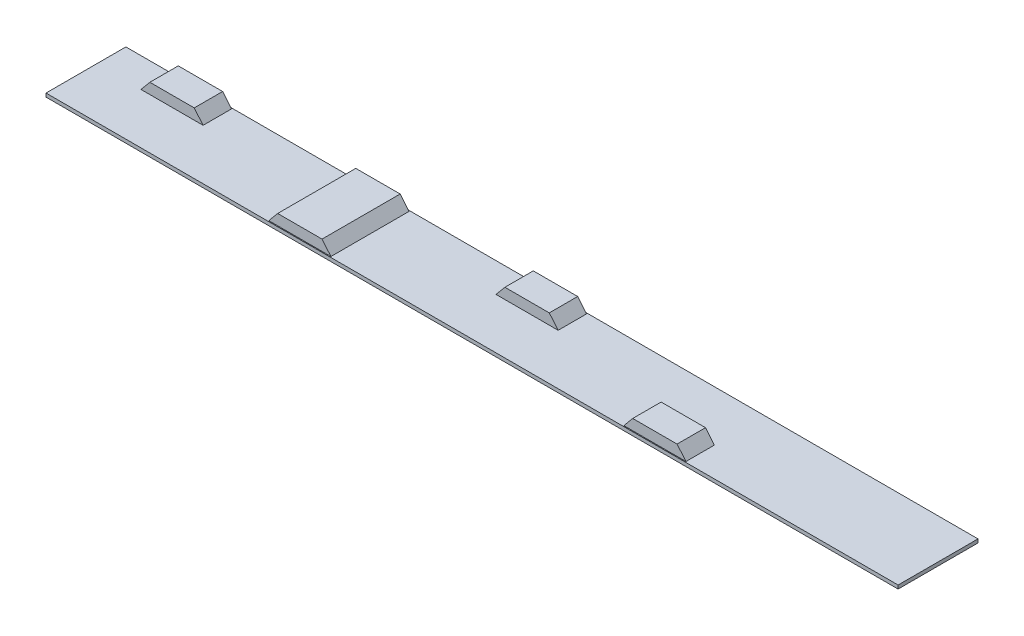
SolidWorks part; units mm, degrees
ref_plane "Front Plane" through (0, 0, 0) normal (0, 0, 1) x (1, 0, 0)
ref_plane "Top Plane" through (0, 0, 0) normal (0, 1, 0) x (1, 0, 0)
ref_plane "Right Plane" through (0, 0, 0) normal (1, 0, 0) x (0, 0, -1)
sketch "Sketch1" plane through (0, 0, 0) normal (0, 1, 0) x (1, 0, 0)
  line L1 (1200, -112.5) -> (-1200, -112.5)
  line L2 (1200, -112.5) -> (1200, 112.5)
  line L3 (1200, 112.5) -> (-1200, 112.5)
  line L4 (-1200, -112.5) -> (-1200, 112.5)
  line L5 (1200, -112.5) -> (-1200, 112.5) construction
  line L6 (1200, 112.5) -> (-1200, -112.5) construction
  point P0 (0, 0)
  dimension "D1" = 2400
  dimension "D2" = 225
extrude "Boss-Extrude1" add sketch "Sketch1" along normal blind 10
sketch "Sketch2" plane through (0, 0, 0) normal (0, 0, 1) x (1, 0, 0)
  line L0 (425, 10) -> (450, 40)
  line L1 (-1200, 10) -> (1200, 10) construction
  line L2 (450, 40) -> (575, 40)
  line L3 (575, 40) -> (600, 10)
  line L4 (600, 10) -> (425, 10)
  line L5 (1200, 10) -> (1200, 0) construction
  dimension "D1" = 175
  dimension "D2" = 125
  dimension "D3" = 30
  dimension "D4" = 600
extrude "Boss-Extrude2" add sketch "Sketch2" along normal blind 80 from offset 30
sketch "Sketch3" plane through (0, 0, 0) normal (0, 0, 1) x (1, 0, 0)
  line L0 (-50, 40) -> (-75, 10)
  line L1 (75, 40) -> (-50, 40)
  line L2 (100, 10) -> (75, 40)
  line L3 (-75, 10) -> (100, 10)
  line L4 (450, 40) -> (425, 10)
  line L5 (575, 40) -> (450, 40)
  line L6 (600, 10) -> (575, 40)
  line L7 (425, 10) -> (600, 10)
  line L8 (450, 40) -> (425, 10) construction
  line L9 (575, 40) -> (450, 40) construction
  line L10 (600, 10) -> (575, 40) construction
  line L11 (425, 10) -> (600, 10) construction
  dimension "D1" = 0
  dimension "D2" = 2
extrude "Boss-Extrude3" add sketch "Sketch3" against normal blind 80 from offset 30 offset against normal yes
sketch "Sketch4" plane through (0, 0, 0) normal (0, 0, 1) x (1, 0, 0)
  line L0 (-550, 40) -> (-575, 10)
  line L1 (-425, 40) -> (-550, 40)
  line L2 (-400, 10) -> (-425, 40)
  line L3 (-575, 10) -> (-400, 10)
  line L4 (450, 40) -> (425, 10)
  line L5 (575, 40) -> (450, 40)
  line L6 (600, 10) -> (575, 40)
  line L7 (425, 10) -> (600, 10)
  line L8 (450, 40) -> (425, 10) construction
  line L9 (575, 40) -> (450, 40) construction
  line L10 (600, 10) -> (575, 40) construction
  line L11 (425, 10) -> (600, 10) construction
  dimension "D1" = 0
extrude "Boss-Extrude4" add sketch "Sketch4" along normal blind 110 and the other way blind 110
sketch "Sketch5" plane through (0, 0, 0) normal (0, 0, 1) x (1, 0, 0)
  line L0 (-1050, 40) -> (-1075, 10)
  line L1 (-1075, 10) -> (-900, 10)
  line L2 (-900, 10) -> (-925, 40)
  line L3 (-925, 40) -> (-1050, 40)
  line L4 (-50, 40) -> (-75, 10)
  line L5 (-75, 10) -> (100, 10)
  line L6 (100, 10) -> (75, 40)
  line L7 (75, 40) -> (-50, 40)
  line L8 (-50, 40) -> (-75, 10) construction
  line L9 (-75, 10) -> (100, 10) construction
  line L10 (100, 10) -> (75, 40) construction
  line L11 (75, 40) -> (-50, 40) construction
  dimension "D1" = 0
extrude "Boss-Extrude5" add sketch "Sketch5" against normal blind 80 from offset 30 offset against normal yes
